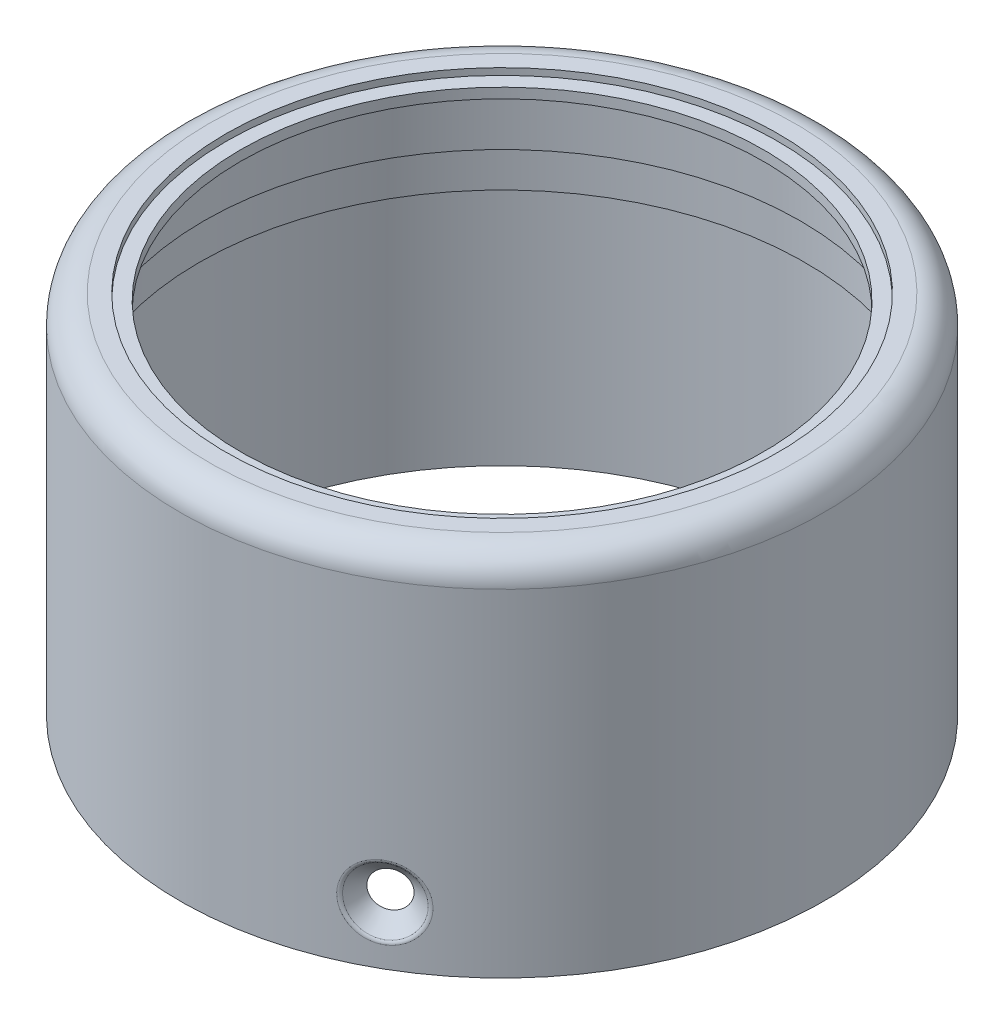
SolidWorks part; units mm, degrees
material "2024 Alloy"
ref_plane "Front Plane" through (0, 0, 0) normal (0, 0, 1) x (1, 0, 0)
ref_plane "Top Plane" through (0, 0, 0) normal (0, 1, 0) x (1, 0, 0)
ref_plane "Right Plane" through (0, 0, 0) normal (1, 0, 0) x (0, 0, -1)
ref_axis "Axis1" through (0, 0, 0) along (0, 1, 0)
sketch "Sketch1" plane through (0, 0, 0) normal (0, 0, 1) x (1, 0, 0)
  line L0 (0, -0.2226) -> (0, -50000.2226) construction
  line L1 (-27.2, 23.3) -> (-27.2, 22.25)
  line L2 (-27.2, 22.25) -> (-29, 22.25)
  line L3 (-29, 22.25) -> (-29, 22)
  line L4 (28.8814, 22) -> (-28.8814, 22) construction
  line L5 (-29, 22) -> (-31, 22)
  line L6 (-31, 22) -> (-31, 15)
  line L9 (-31, 15) -> (-31.5, 15)
  line L10 (-31.5, 15) -> (-31.5, 11)
  line L11 (-31.5, 11) -> (-31.75, 11)
  line L16 (-31.75, 11) -> (-31.75, -14)
  line L17 (-31.75, -14) -> (-33.5, -14)
  line L18 (-33.5, -14) -> (-33.5, 21)
  line L19 (-30.5, 24) -> (-28.7, 24)
  line L20 (-28.7, 24) -> (-28.7, 23.3)
  line L21 (-28.7, 23.3) -> (-27.2, 23.3)
  line L22 (-27, 23.5) -> (-27, 22) construction
  line L23 (-28.5, 23.5) -> (28.5, 23.5) construction
  line L24 (-28.5, 24.0977) -> (-28.5, 23.5) construction
  line L25 (27.5858, 25) -> (-27.5858, 25) construction
  line L26 (30.8, 22) -> (-30.8, 22) construction
  line L27 (-30.4, -4) -> (30.4, -4) construction
  line L32 (31.5, 15) -> (-31.5, 15) construction
  arc A0 (-33.5, 21) -> (-30.5, 24) centre (-30.5, 21) cw
  point P11 (0, 0)
  point P16 (0, 0)
  point P17 (-31.4, 9.6869)
  point P18 (-31.918, 10.934)
  point P19 (-29.1116, 22)
  point P34 (-31.5, 9.968)
  dimension "D9" = 3
  dimension "D1" = 62
  dimension "D2" = 0.25
  dimension "D3" = 0.2
  dimension "D4" = 0.2
  dimension "D5" = 0.2
  dimension "D6" = 1
  dimension "D7" = 2.5
  dimension "D8" = 0.25
  dimension "D10" = 63
  dimension "D11" = 4
  dimension "D12" = 2
  dimension "D13" = 10
revolve "Revolve1" add sketch "Sketch1" angle 360 about L0
sketch "Sketch4" plane through (0, 0, 0) normal (0, 0, 1) x (1, 0, 0)
  line L0 (-29.7689, -8) -> (49970.2311, -8) construction
  line L1 (-33.5, -8) -> (-25.2975, -8)
  line L2 (-25.2975, -8) -> (-25.2975, -6.4)
  line L3 (-25.2975, -6.4) -> (-31.5, -6.4)
  line L4 (-31.5, -6.4) -> (-33.5, -4.4)
  line L5 (-33.5, -14) -> (-33.5, 21) construction
  line L6 (-33.5, -4.4) -> (-33.5, -8)
  line L7 (-31.75, -14) -> (-33.5, -14) construction
  point P9 (-31.2306, -7.0895)
  point P10 (-31, -7.03)
  point P13 (-25.2975, -6)
  dimension "D1" = 2
  dimension "D2" = 45
  dimension "D3" = 3.2
  dimension "D4" = 6
revolve "Cut-Revolve1" cut sketch "Sketch4" angle 360 about L0
pattern_circular "CirPattern2" count 3 over 360 about axis through (0, 0, 0) along (0, 1, 0) of "Cut-Revolve1"
sketch "Sketch2" [suppressed] plane through (0, 0, 0) normal (0, 0, 1) x (1, 0, 0)
  line L1 (-8, 10.5) -> (8, 10.5)
  line L2 (-10, 8.5) -> (-10, -1.4)
  line L3 (-8, -3.4) -> (8, -3.4)
  line L4 (10, 8.5) -> (10, -1.4)
  line L5 (-10, 10.5) -> (10, -3.4) construction
  line L6 (-10, -3.4) -> (10, 10.5) construction
  line L8 (-31.5, 11) -> (31.5, 11) construction
  arc A0 (8, 10.5) -> (10, 8.5) centre (8, 8.5) cw
  arc A1 (-10, -1.4) -> (-8, -3.4) centre (-8, -1.4) ccw
  arc A2 (-8, 10.5) -> (-10, 8.5) centre (-8, 8.5) ccw
  arc A3 (8, -3.4) -> (10, -1.4) centre (8, -1.4) ccw
  point P0 (0, 3.55)
  dimension "D1" = 2
  dimension "D2" = 0.5
  dimension "D3" = 1
  dimension "D4" = 20
extrude "Cut-Extrude1" [suppressed] cut sketch "Sketch2" against normal through all
pattern_circular "CirPattern1" [suppressed] count 6 over 360 about axis through (0, 0, 0) along (0, 1, 0)
fillet "Fillet1" radius 0.5 3 edges at (18.1833, -4.8634, -28.1357) (-33.3762, -6.0498, 2.8776) (19.0074, -5.7446, 27.5857)
